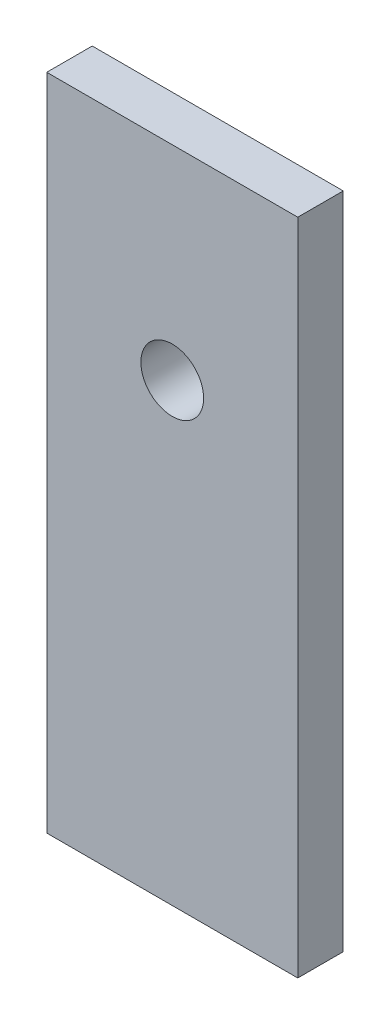
SolidWorks part; units mm, degrees
material "Бальса"
ref_plane "Спереди" through (0, 0, 0) normal (0, 0, 1) x (1, 0, 0)
ref_plane "Сверху" through (0, 0, 0) normal (0, 1, 0) x (1, 0, 0)
ref_plane "Справа" through (0, 0, 0) normal (1, 0, 0) x (0, 0, -1)
sketch "Эскиз1" plane through (0, 0, 0) normal (0, 0, 1) x (1, 0, 0)
  line L0 (16, 84) -> (16, 0) construction
  line L1 (0, 0) -> (32, 0)
  line L2 (0, 0) -> (0, 84)
  line L3 (0, 84) -> (32, 84)
  line L4 (32, 0) -> (32, 84)
  line L5 (16, 42) -> (32, 42) construction
  circle A0 centre (16, 58) radius 4
  dimension "D3" = 8
  dimension "D1" = 84
  dimension "D2" = 32
  dimension "D4" = 16
extrude "Бобышка-Вытянуть1" add sketch "Эскиз1" along normal blind 5.8
